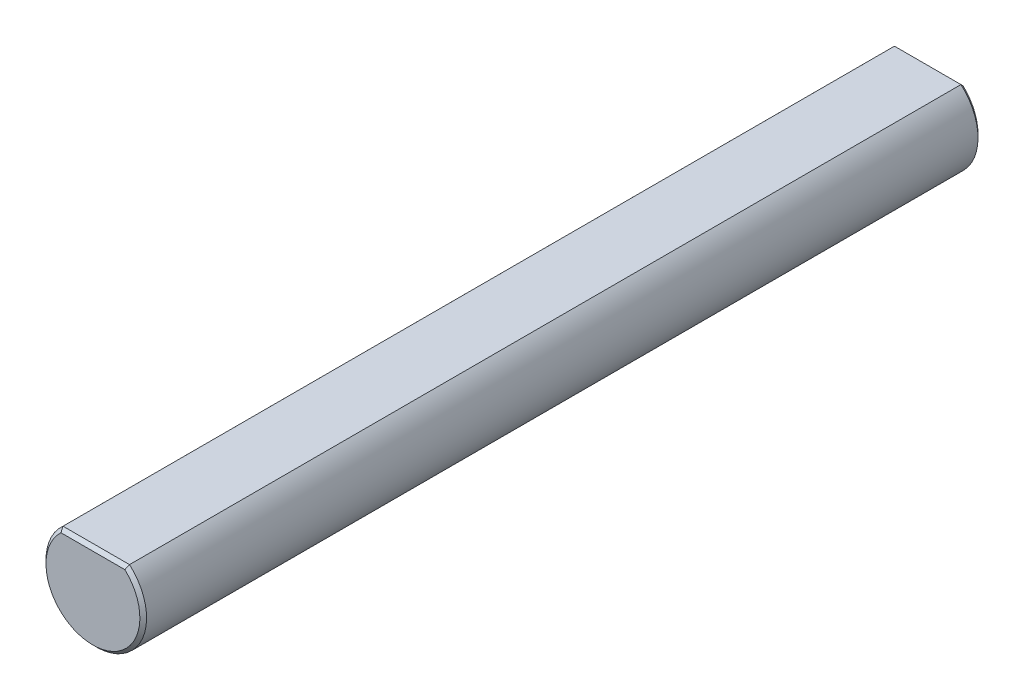
SolidWorks part; units mm, degrees
ref_plane "前基準面" through (0, 0, 0) normal (0, 0, 1) x (1, 0, 0)
ref_plane "上基準面" through (0, 0, 0) normal (0, 1, 0) x (1, 0, 0)
ref_plane "右基準面" through (0, 0, 0) normal (1, 0, 0) x (0, 0, -1)
ref_plane "平面1" through (0, 0, 52) normal (0, 0, 1) x (1, 0, 0)
sketch "草圖1" plane through (0, 0, 52) normal (0, 0, 1) x (1, 0, 0)
  line L0 (1.9843, 2.25) -> (-1.9843, 2.25)
  arc A0 (-1.9843, 2.25) -> (1.9843, 2.25) centre (0, 0) ccw
  dimension "D1" = 3
extrude "填料-伸長1" add sketch "草圖1" against normal blind 50
chamfer "導角1" distance 0.2 angle 45 4 edges at (0, 2.25, 2) (0, -3, 2) (0, 2.25, 52) (0, -3, 52)
